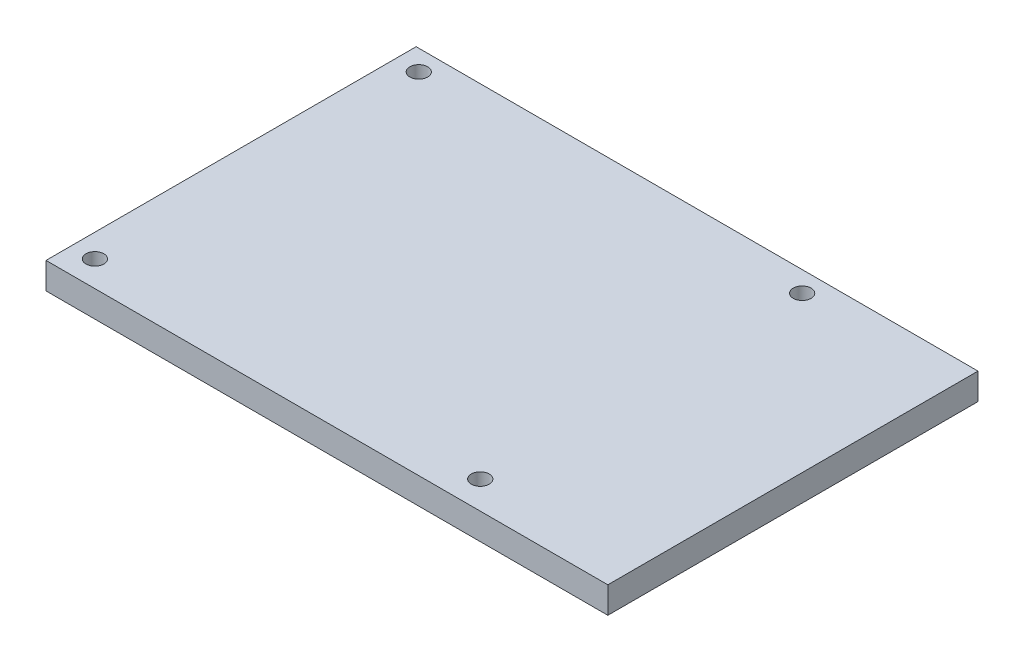
SolidWorks part; units mm, degrees
ref_plane "前视基准面" through (0, 0, 0) normal (0, 0, 1) x (1, 0, 0)
ref_plane "上视基准面" through (0, 0, 0) normal (0, 1, 0) x (1, 0, 0)
ref_plane "右视基准面" through (0, 0, 0) normal (1, 0, 0) x (0, 0, -1)
other "Configuration Table"
sketch "草图1" plane through (0, 0, 0) normal (0, 1, 0) x (1, 0, 0)
  line L1 (-49.2662, 17.7743) -> (35.7338, 17.7743)
  line L2 (-49.2662, 17.7743) -> (-49.2662, -38.2257)
  line L3 (-49.2662, -38.2257) -> (35.7338, -38.2257)
  line L4 (35.7338, 17.7743) -> (35.7338, -38.2257)
  circle A0 centre (-45.7662, 14.6704) radius 1.35
  circle A1 centre (12.2338, 14.6704) radius 1.35
  circle A2 centre (-45.7662, -34.3296) radius 1.35
  circle A3 centre (12.233, -34.0257) radius 1.35
  point P12 (0, 0)
  point P13 (0, 0)
  point P14 (-44.5966, 20.7403)
  point P15 (14.9456, -32.1558)
  point P16 (-49.0723, -27.9558)
  point P17 (-49.0715, 20.7403)
  point P18 (-44.4138, 20.7403)
  point P19 (-48.4712, 20.7403)
  point P20 (0, 0)
  point P21 (0, 0)
  point P22 (-42.4602, 20.7403)
  point P23 (0, 0)
  point P24 (-42.4602, 20.7403)
  point P25 (-51.3265, 20.7403)
  point P26 (0, 0)
  point P27 (-49.974, 28.1954)
  point P28 (-26.2302, 21.7334)
  point P29 (-45.7662, 14.6704)
  dimension "D3" = 2.7
  dimension "D4" = 2.7
  dimension "D5" = 2.7
  dimension "D6" = 2.7
  dimension "D1" = 85
  dimension "D2" = 56
  dimension "D7" = 58
  dimension "D8" = 58
  dimension "D9" = 49
  dimension "D10" = 52.8961
  dimension "D11" = 4.2
  dimension "D12" = 3.5
extrude "凸台-拉伸1" add sketch "草图1" along normal blind 4
